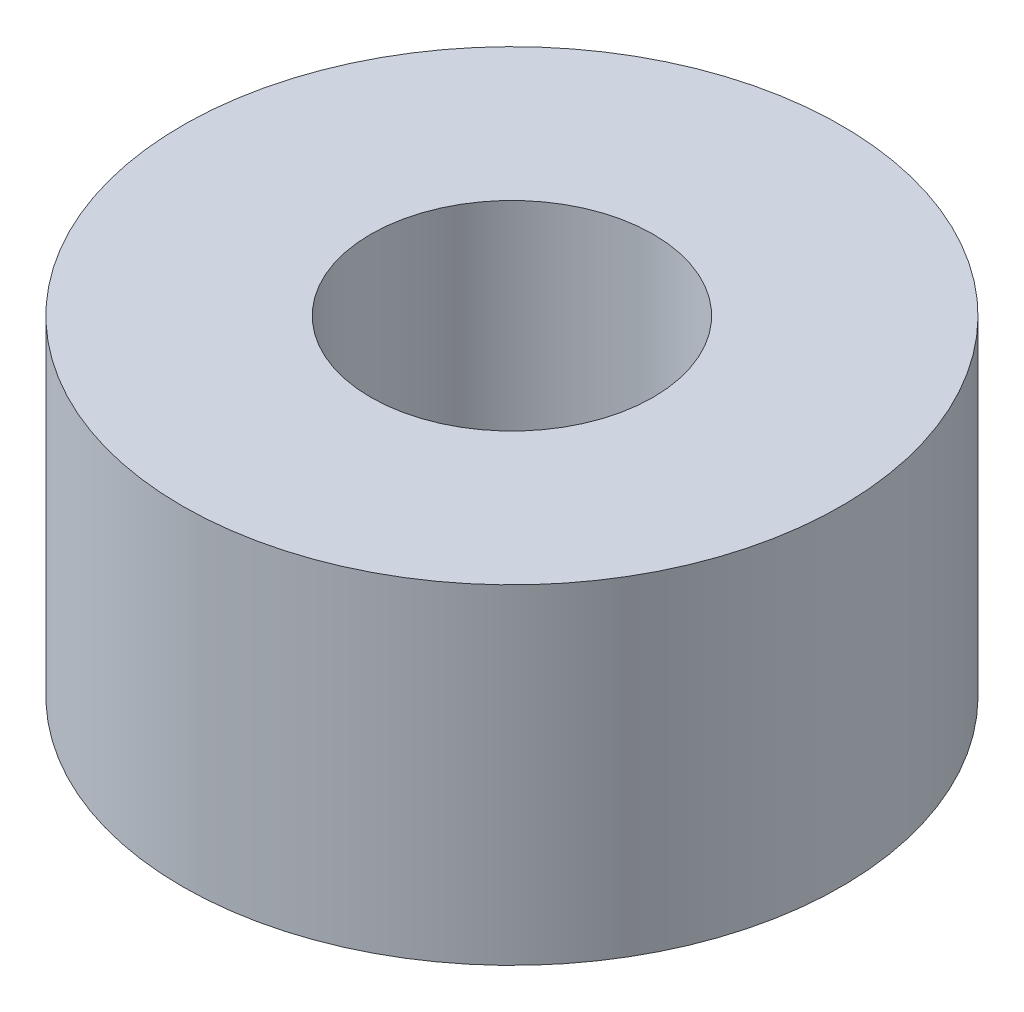
SolidWorks part; units mm, degrees
ref_plane "Front Plane" through (0, 0, 0) normal (0, 0, 1) x (1, 0, 0)
ref_plane "Top Plane" through (0, 0, 0) normal (0, 1, 0) x (1, 0, 0)
ref_plane "Right Plane" through (0, 0, 0) normal (1, 0, 0) x (0, 0, -1)
sketch "Sketch1" plane through (0, 0, 0) normal (0, 1, 0) x (1, 0, 0)
  circle A0 centre (0, 0) radius 8.89
  circle A1 centre (0, 0) radius 3.81
  dimension "D1" = 7.62
  dimension "D2" = 17.78
extrude "Boss-Extrude1" add sketch "Sketch1" along normal blind 8.89
